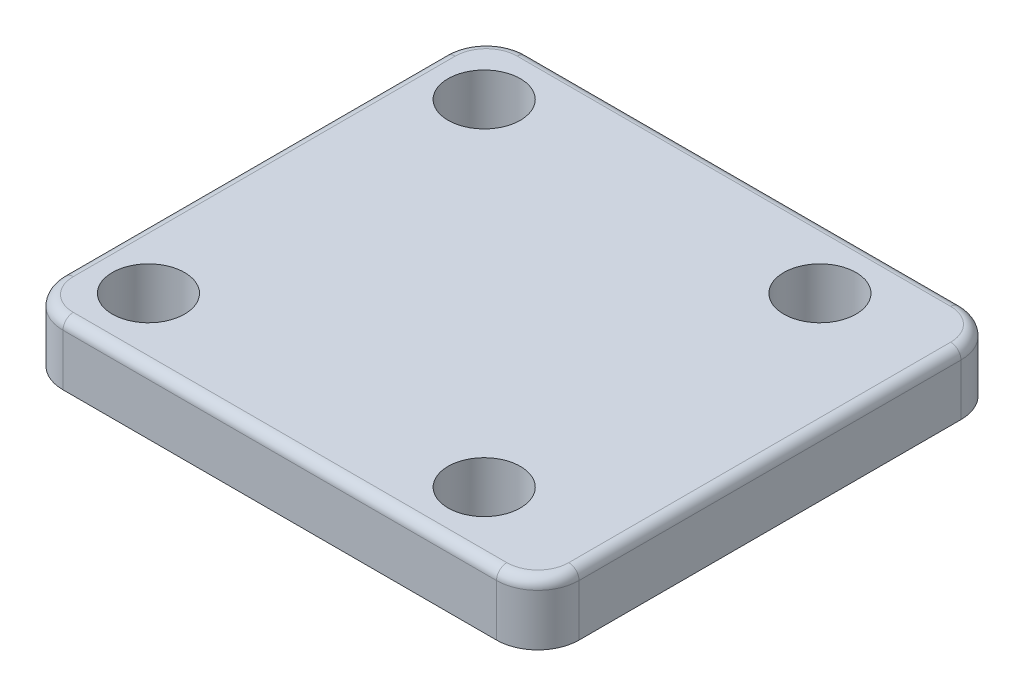
SolidWorks part; units mm, degrees
ref_plane "Front Plane" through (0, 0, 0) normal (0, 0, 1) x (1, 0, 0)
ref_plane "Top Plane" through (0, 0, 0) normal (0, 1, 0) x (1, 0, 0)
ref_plane "Right Plane" through (0, 0, 0) normal (1, 0, 0) x (0, 0, -1)
sketch "Sketch1" plane through (0, 0, 0) normal (0, 1, 0) x (1, 0, 0)
  line L1 (-18.3057, 22.5) -> (23.6943, 22.5)
  line L2 (-22.3057, 18.5) -> (-22.3057, -18.5)
  line L3 (-18.3057, -22.5) -> (23.6943, -22.5)
  line L4 (27.6943, 18.5) -> (27.6943, -18.5)
  arc A0 (23.6943, 22.5) -> (27.6943, 18.5) centre (23.6943, 18.5) cw
  arc A1 (-22.3057, -18.5) -> (-18.3057, -22.5) centre (-18.3057, -18.5) ccw
  arc A2 (23.6943, -22.5) -> (27.6943, -18.5) centre (23.6943, -18.5) ccw
  arc A3 (-18.3057, 22.5) -> (-22.3057, 18.5) centre (-18.3057, 18.5) ccw
  point P7 (27.6943, 22.5)
  point P10 (-22.3057, -22.5)
  point P15 (-22.3057, 22.5)
  dimension "D5" = 4
  dimension "D1" = 50
  dimension "D2" = 45
  dimension "D3" = 22.5
  dimension "D4" = 22.3057
extrude "Boss-Extrude1" add sketch "Sketch1" along normal blind 6
fillet "Fillet1" radius 1 8 edges at (27.6943, 6, 0) (26.5228, 6, 21.3284) (2.6943, 6, 22.5) (-21.1341, 6, 21.3284) (-22.3057, 6, 0) (-21.1341, 6, -21.3284) (2.6943, 6, -22.5) (26.5228, 6, -21.3284)
sketch "Sketch2" plane through (0, 0, 0) normal (0, -1, 0) x (1, 0, 0)
  circle A0 centre (0, 0) radius 16
  dimension "D1" = 32
extrude "Boss-Extrude2" add sketch "Sketch2" along normal blind 2
chamfer "Chamfer1" distance 1 angle 45 1 edges at (0, -2, -16)
sketch "Sketch3" plane through (0, 6, 0) normal (0, 1, 0) x (1, 0, 0)
  line L0 (0, 0) -> (-25.1199, 0) construction
  line L1 (0, 0) -> (-16.2635, 16.2635) construction
  circle A0 centre (0, 0) radius 23 construction
  circle A1 centre (-16.2635, 16.2635) radius 3.5
  circle A2 centre (16.2635, 16.2635) radius 3.5
  circle A3 centre (16.2635, -16.2635) radius 3.5
  circle A4 centre (-16.2635, -16.2635) radius 3.5
  point P15 (0, 0)
  dimension "D1" = 46
  dimension "D2" = 7
  dimension "D3" = 45
  dimension "D4" = 4
extrude "Cut-Extrude1" cut sketch "Sketch3" against normal through all
